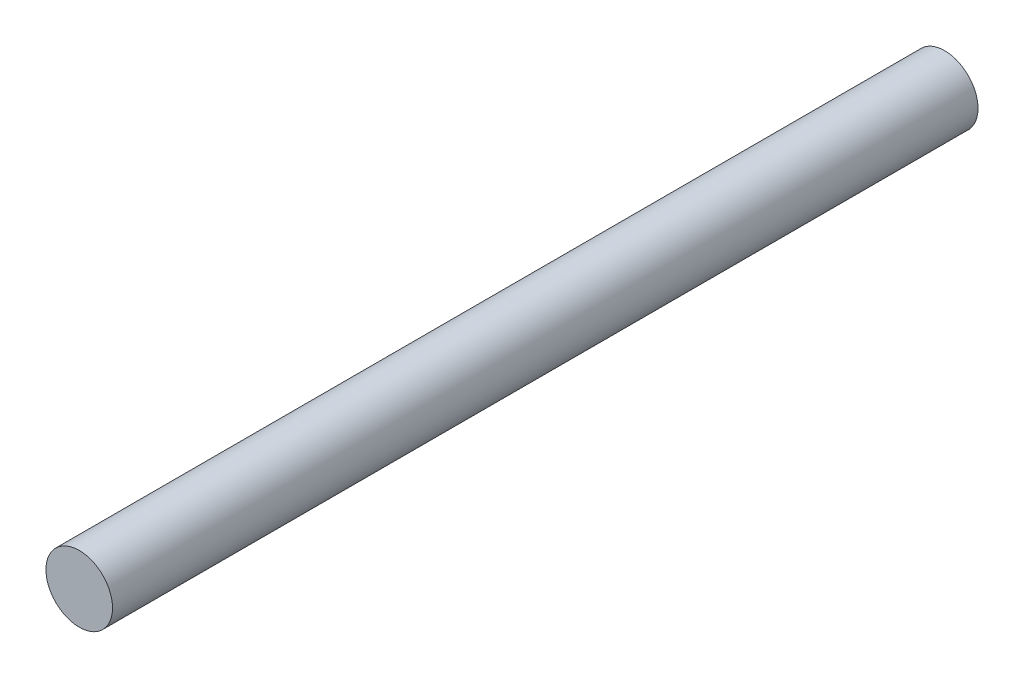
SolidWorks part; units mm, degrees
ref_plane "Alzado" through (0, 0, 0) normal (0, 0, 1) x (1, 0, 0)
ref_plane "Planta" through (0, 0, 0) normal (0, 1, 0) x (1, 0, 0)
ref_plane "Vista lateral" through (0, 0, 0) normal (1, 0, 0) x (0, 0, -1)
sketch "Croquis1" plane through (0, 0, 0) normal (0, 0, 1) x (1, 0, 0)
  circle A0 centre (0, 0) radius 10
  dimension "D1" = 20
extrude "Saliente-Extruir1" add sketch "Croquis1" along normal mid plane 260
